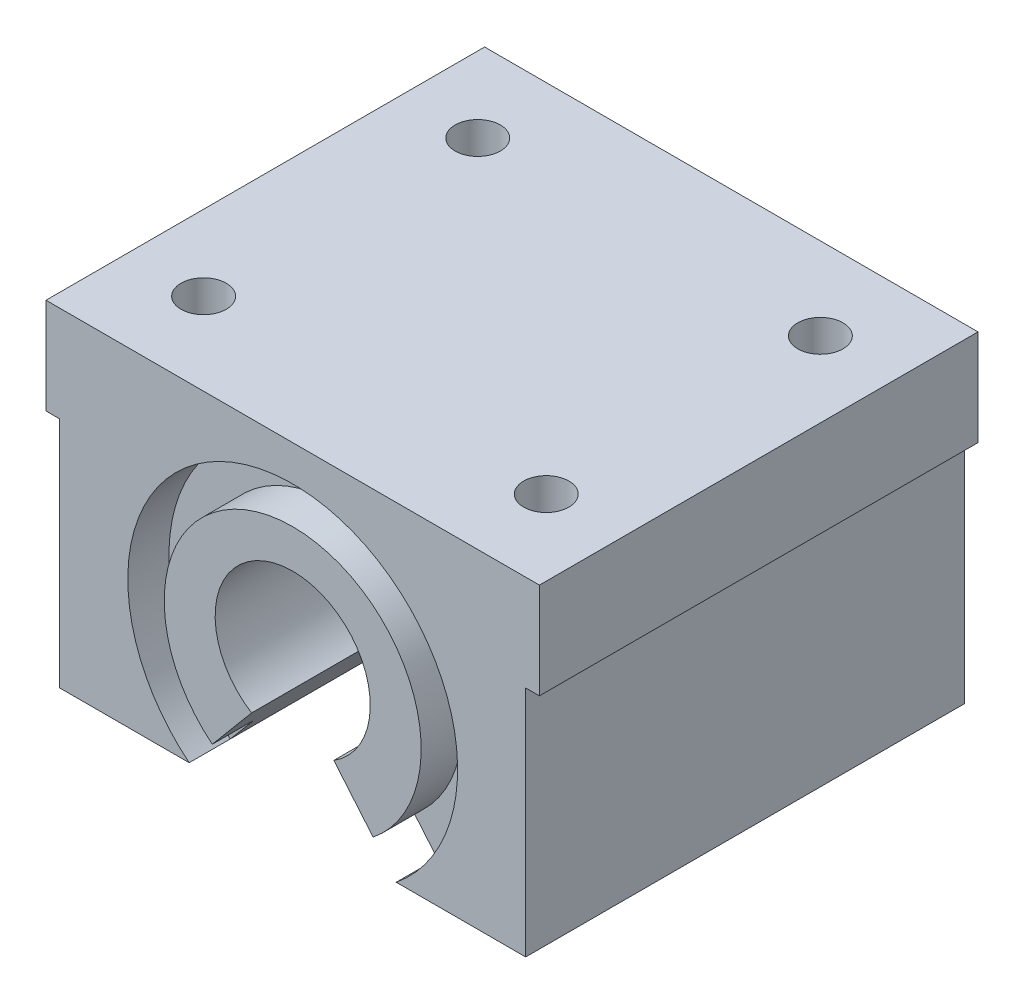
SolidWorks part; units mm, degrees
ref_plane "前视基准面" through (0, 0, 0) normal (0, 0, 1) x (1, 0, 0)
ref_plane "上视基准面" through (0, 0, 0) normal (0, 1, 0) x (1, 0, 0)
ref_plane "右视基准面" through (0, 0, 0) normal (1, 0, 0) x (0, 0, -1)
sketch "草图1" plane through (0, 0, 0) normal (0, 0, 1) x (1, 0, 0)
  line L0 (-18, 0) -> (18, 0)
  line L1 (-18, 0) -> (-18, -7)
  line L2 (18, 0) -> (18, -7)
  line L3 (-18, -7) -> (-17, -7)
  line L4 (18, -7) -> (17, -7)
  line L5 (-17, -7) -> (-17, -24)
  line L6 (17, -7) -> (17, -24)
  line L7 (-3, 21.2366) -> (-3, -29.8548) construction
  line L8 (3, 21.2366) -> (3, -29.9379) construction
  line L9 (-27.506, -15) -> (27.9884, -15) construction
  line L10 (0, -1000) -> (0, 49000) construction
  line L11 (0, -15) -> (-11.0154, -28.1277) construction
  line L12 (0, -15) -> (11.2518, -28.4093) construction
  line L13 (-17, -24) -> (-7.5519, -24)
  line L14 (17, -24) -> (7.5519, -24)
  line L15 (-3, -18.5753) -> (-7.5519, -24)
  line L16 (3, -18.5753) -> (7.5519, -24)
  arc A0 (-3, -18.5753) -> (3, -18.5753) centre (0, -13.7757) cw
  dimension "D9" = 1
  dimension "D1" = 36
  dimension "D2" = 7
  dimension "D3" = 7
  dimension "D4" = 3
  dimension "D5" = 6
  dimension "D6" = 15
  dimension "D7" = 17
  dimension "D8" = 18
  dimension "D10" = 40
  dimension "D11" = 40
extrude "凸台-拉伸1" add sketch "草图1" along normal mid plane 32
sketch "草图2" plane through (0, 0, 16) normal (0, 0, 1) x (1, 0, 0)
  line L0 (-7.5519, -24) -> (-3, -18.5753) construction
  line L1 (3, -18.5753) -> (7.5519, -24) construction
  line L2 (-7.5519, -24) -> (-5.8661, -21.991)
  line L3 (5.8661, -21.991) -> (7.5519, -24)
  arc A0 (-7.5519, -24) -> (7.5519, -24) centre (0, -14.6349) cw
  arc A1 (-5.8661, -21.991) -> (5.8661, -21.991) centre (0, -14.6801) cw
extrude "切除-拉伸1" cut sketch "草图2" against normal blind 3
sketch "草图3" plane through (0, 0, 0) normal (0, 1, 0) x (1, 0, 0)
  line L0 (0, -1000) -> (0, 49000) construction
  line L1 (-1000, 0) -> (49000, 0) construction
  circle A0 centre (-12.5, -10) radius 2
  dimension "D1" = 12.5
  dimension "D2" = 10
hole_wizard "M4 螺纹孔的螺纹孔钻头1" positions "3D草图1" profile "草图4" hole size "M4" standard "GB"
sketch3d "3D草图1"
  point P0 (-12.5, 0, 10)
sketch "草图4" plane through (-12.5, 0, 10) normal (1, 0, 0) x (0, 0, 1)
  line L0 (0, 0) -> (0, 10.9914)
  line L1 (0, 10.9914) -> (1.65, 10)
  line L2 (1.65, 10) -> (1.65, 0)
  line L5 (1.65, 0) -> (0, 0)
  line L10 (0, 10.9914) -> (-1.65, 10) construction
  line L11 (0, -6.35) -> (0, 107.95) construction
  dimension "孔直径" = 3.3
  dimension "孔深度" = 10
  dimension "导头角度" = 118
mirror "镜向1" about plane through (0, 0, 0) normal (0, 0, 1) of "M4 螺纹孔的螺纹孔钻头1"
mirror "镜向2" about plane through (0, 0, 0) normal (1, 0, 0) of "镜向1", "M4 螺纹孔的螺纹孔钻头1"
